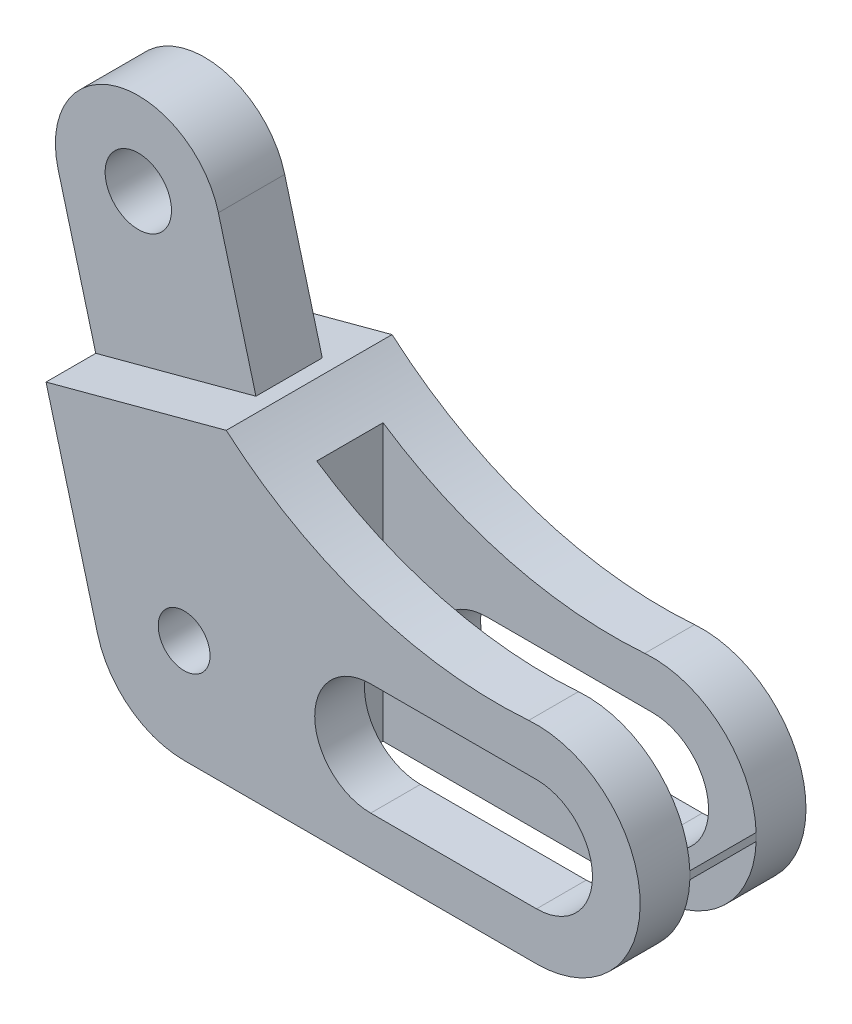
SolidWorks part; units mm, degrees
ref_plane "Front Plane" through (0, 0, 0) normal (0, 0, 1) x (1, 0, 0)
ref_plane "Top Plane" through (0, 0, 0) normal (0, 1, 0) x (1, 0, 0)
ref_plane "Right Plane" through (0, 0, 0) normal (1, 0, 0) x (0, 0, -1)
sketch "Sketch1" plane through (0, 0, 0) normal (0, 0, 1) x (1, 0, 0)
  line L0 (0, 71.2136) -> (0, -75.9676) construction
  line L1 (0, 0) -> (138.2936, 0) construction
  line L2 (0, -25) -> (85, -25)
  line L3 (10.1533, 49.0408) -> (-33.3134, 37.394)
  line L4 (-33.3134, 37.394) -> (-20.8901, -8.9705)
  line L5 (85, 0.0028) -> (45, 0) construction
  line L6 (85.0009, -13.4972) -> (45.0009, -13.5)
  line L7 (84.9991, 13.5028) -> (44.9991, 13.5)
  line L8 (0, 0) -> (-11.5801, 43.2174) construction
  arc A0 (85, -25) -> (83.1194, 24.9348) centre (85, 0.0028) ccw
  arc A1 (83.1194, 24.9348) -> (10.1533, 49.0408) centre (75.5981, 124.6515) cw
  arc A2 (-20.8901, -8.9705) -> (0, -25) centre (0, -3.373) ccw
  circle A3 centre (0, 0) radius 6.25
  arc A4 (85.0009, -13.4972) -> (84.9991, 13.5028) centre (85, 0.0028) ccw
  arc A5 (44.9991, 13.5) -> (45.0009, -13.5) centre (45, 0) ccw
  point P15 (65, 0.0014)
  point P21 (-86.3587, 58.3894)
  dimension "D3" = 25.0028
  dimension "D4" = 100
  dimension "D7" = 12.5
  dimension "D9" = 13.5
  dimension "D1" = 85
  dimension "D2" = 25
  dimension "D5" = 45
  dimension "D6" = 48
  dimension "D8" = 40
  dimension "D10" = 15
extrude "Boss-Extrude1" add sketch "Sketch1" along normal mid plane 40
sketch "Sketch2" plane through (0, 0, 0) normal (0, 0, 1) x (1, 0, 0)
  line L0 (-33.3134, 37.394) -> (-42.3721, 71.2014)
  line L1 (-33.3134, 37.394) -> (5.3236, 47.7467)
  line L2 (-3.735, 81.5541) -> (5.3236, 47.7467)
  line L3 (10.1533, 49.0408) -> (-33.3134, 37.394) construction
  arc A0 (-3.735, 81.5541) -> (-42.3721, 71.2014) centre (-23.0535, 76.3777) ccw
  circle A1 centre (-23.0535, 76.3777) radius 8
  dimension "D3" = 16
  dimension "D1" = 35
  dimension "D2" = 40
extrude "Boss-Extrude2" add sketch "Sketch2" along normal mid plane 16
ref_plane "Plane1" through (109.9851, 0, 0) normal (1, 0, 0) x (0, 0, -1)
sketch "Sketch3" plane through (109.9851, 0, 0) normal (1, 0, 0) x (0, 0, -1)
  line L0 (-20, -25) -> (20, -25) construction
  line L1 (-8, 141.2442) -> (8, 141.2442)
  line L2 (-8, 141.2442) -> (-8, -191.2442)
  line L3 (-8, -191.2442) -> (8, -191.2442)
  line L4 (8, 141.2442) -> (8, -191.2442)
  line L5 (-8, 141.2442) -> (8, -191.2442) construction
  line L6 (-8, -191.2442) -> (8, 141.2442) construction
  point P0 (0, -25)
  dimension "D1" = 16
extrude "Cut-Extrude1" cut sketch "Sketch3" against normal blind 90 contours L2 L1 L4 L3
